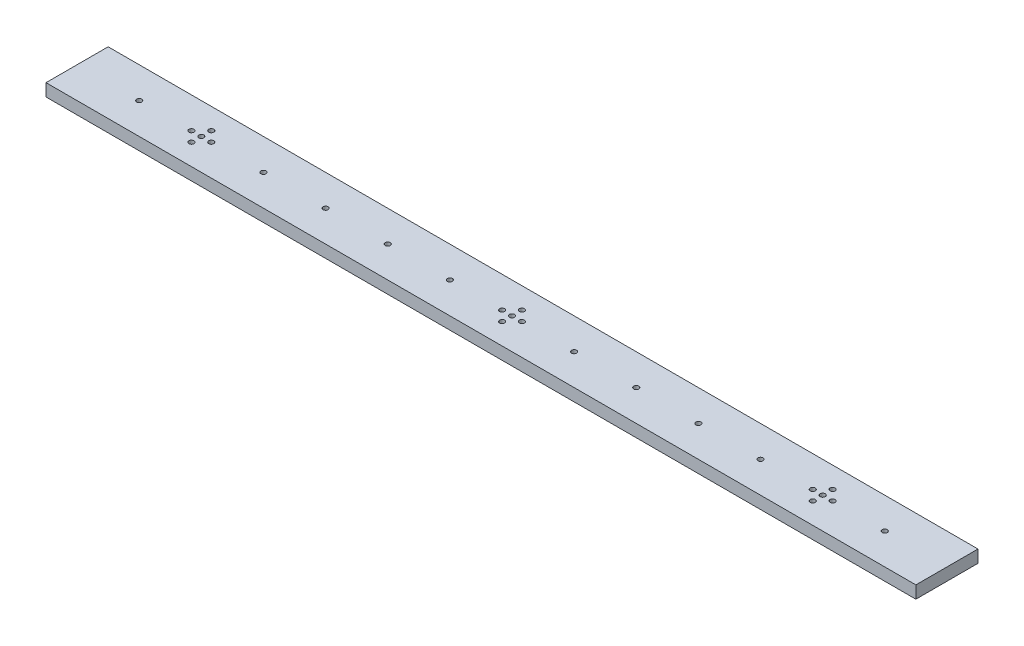
SolidWorks part; units mm, degrees
ref_plane "前视基准面" through (0, 0, 0) normal (0, 0, 1) x (1, 0, 0)
ref_plane "上视基准面" through (0, 0, 0) normal (0, 1, 0) x (1, 0, 0)
ref_plane "右视基准面" through (0, 0, 0) normal (1, 0, 0) x (0, 0, -1)
sketch "草图1" plane through (0, 0, 0) normal (0, 1, 0) x (1, 0, 0)
  line L1 (-350, 25) -> (350, 25)
  line L2 (-350, 25) -> (-350, -25)
  line L3 (-350, -25) -> (350, -25)
  line L4 (350, 25) -> (350, -25)
  line L5 (-350, 25) -> (350, -25) construction
  line L6 (-350, -25) -> (350, 25) construction
  point P0 (0, 0)
  dimension "D1" = 700
  dimension "D2" = 50
extrude "凸台-拉伸1" add sketch "草图1" along normal blind 10
sketch "草图2" plane through (0, 10, 0) normal (0, 1, 0) x (1, 0, 0)
  line L0 (-350, 0) -> (541.3083, 0) construction
  line L1 (-350, 25) -> (-350, -25) construction
  circle A0 centre (-350, 0) radius 2.05 construction
  circle A15 centre (-300, 0) radius 2.05
  circle A16 centre (-250, 0) radius 2.05
  circle A17 centre (-200, 0) radius 2.05
  circle A18 centre (-150, 0) radius 2.05
  circle A19 centre (-100, 0) radius 2.05
  circle A20 centre (-50, 0) radius 2.05
  circle A21 centre (0, 0) radius 2.05
  circle A22 centre (50, 0) radius 2.05
  circle A23 centre (100, 0) radius 2.05
  circle A24 centre (150, 0) radius 2.05
  circle A25 centre (200, 0) radius 2.05
  circle A26 centre (250, 0) radius 2.05
  circle A28 centre (300, 0) radius 2.05 construction
  circle A29 centre (300, 0) radius 2.05
  circle A30 centre (350, 0) radius 2.05 construction
  circle A33 centre (400, 0) radius 2.05 [skipped]
  circle A34 centre (450, 0) radius 2.05 [skipped]
  dimension "D1" = 4.1
  dimension "D2" = 14
  dimension "D3" = 5
extrude "切除-拉伸2" cut sketch "草图2" against normal through all
sketch "草图3" plane through (0, 10, 0) normal (0, 1, 0) x (1, 0, 0)
  line L0 (-250, 0) -> (-227.6132, 0) construction
  circle A0 centre (-242, 0) radius 2.05
  circle A1 centre (-258, 0) radius 2.05
  circle A2 centre (-8, 0) radius 2.05
  circle A3 centre (8, 0) radius 2.05
  circle A4 centre (242, 0) radius 2.05
  circle A5 centre (258, 0) radius 2.05
  circle A6 centre (-250, 0) radius 2.05 construction
  circle A7 centre (-250, 8) radius 2.05
  circle A8 centre (-250, -8) radius 2.05
  circle A9 centre (0, 8) radius 2.05
  circle A10 centre (0, -8) radius 2.05
  circle A11 centre (250, 8) radius 2.05
  circle A12 centre (250, -8) radius 2.05
  dimension "D1" = 4.1
  dimension "D2" = 4.1
  dimension "D4" = 8
  dimension "D5" = 8
  dimension "D6" = 4.1
  dimension "D7" = 4.1
  dimension "D8" = 8
  dimension "D9" = 8
  dimension "D3" = 3
extrude "切除-拉伸3" cut sketch "草图3" against normal through all
